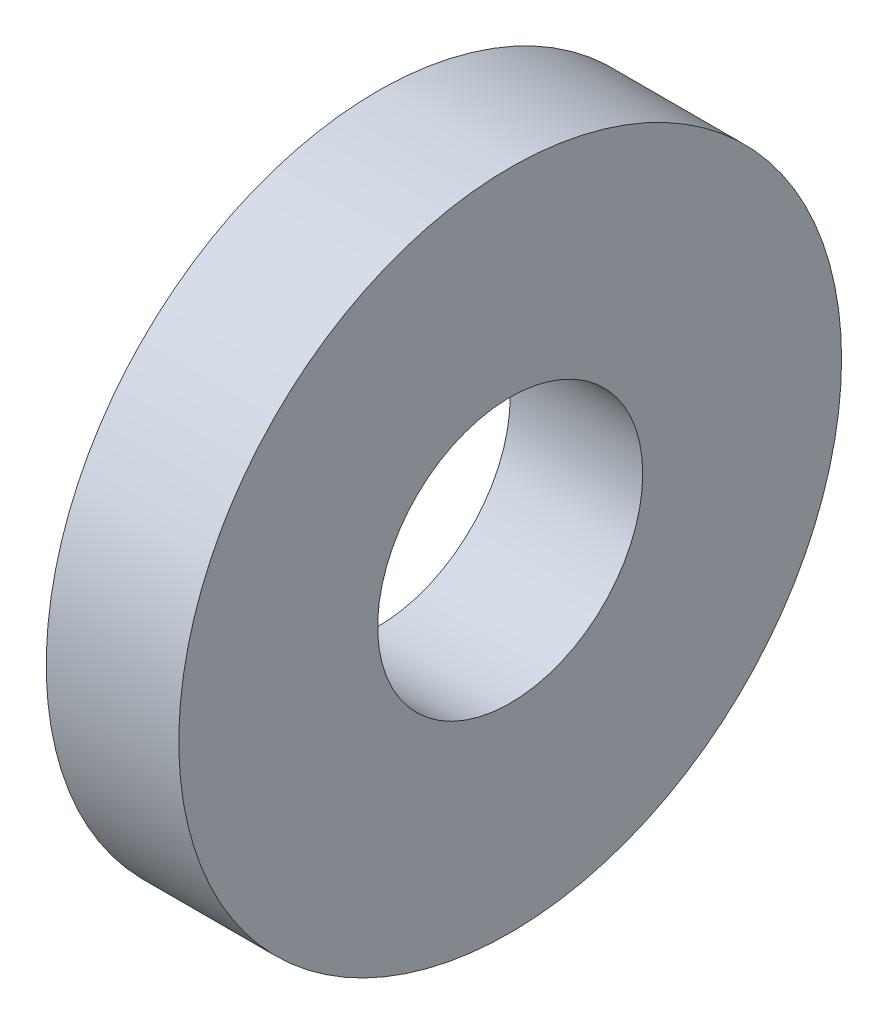
SolidWorks part; units mm, degrees
ref_plane "Front Plane" through (0, 0, 0) normal (0, 0, 1) x (1, 0, 0)
ref_plane "Top Plane" through (0, 0, 0) normal (0, 1, 0) x (1, 0, 0)
ref_plane "Right Plane" through (0, 0, 0) normal (1, 0, 0) x (0, 0, -1)
sketch "Sketch4" plane through (0, 0, 0) normal (1, 0, 0) x (0, 0, -1)
  circle A0 centre (0, 0) radius 12.5
  circle A1 centre (0, 0) radius 5
  dimension "D1" = 10
  dimension "D2" = 25
extrude "Boss-Extrude1" add sketch "Sketch4" along normal mid plane 5
